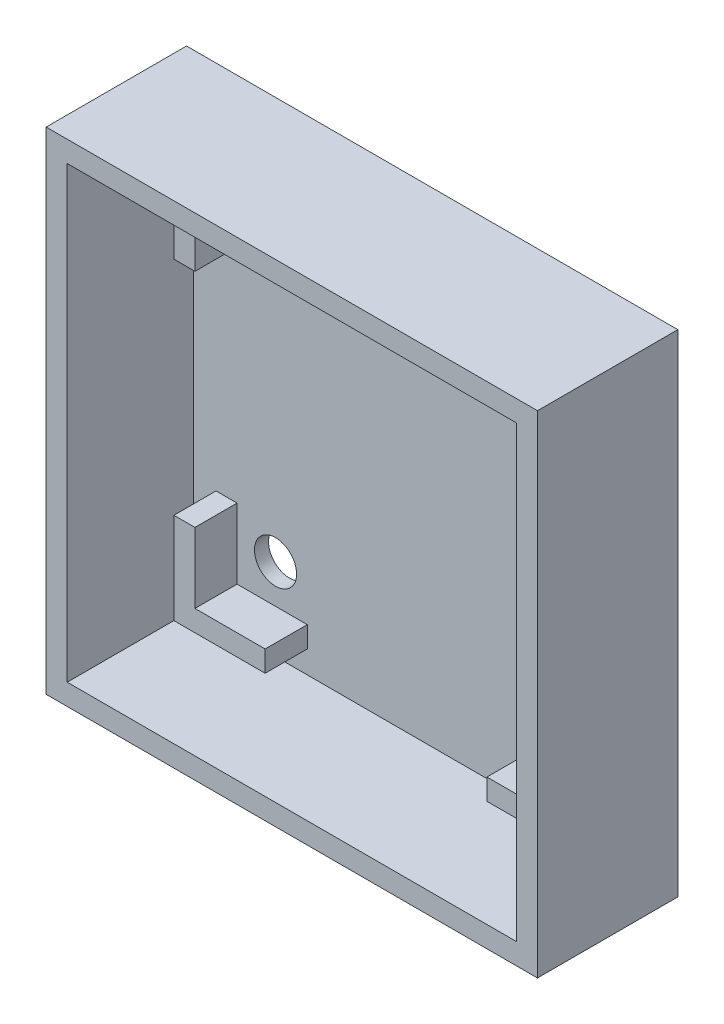
SolidWorks part; units mm, degrees
ref_plane "Front Plane" through (0, 0, 0) normal (0, 0, 1) x (1, 0, 0)
ref_plane "Top Plane" through (0, 0, 0) normal (0, 1, 0) x (1, 0, 0)
ref_plane "Right Plane" through (0, 0, 0) normal (1, 0, 0) x (0, 0, -1)
sketch "Sketch1" plane through (0, 0, 0) normal (0, 0, 1) x (1, 0, 0)
  line L1 (0, 0) -> (35, 0)
  line L2 (0, 0) -> (0, -35)
  line L3 (0, -35) -> (35, -35)
  line L4 (35, 0) -> (35, -35)
  dimension "D1" = 35
  dimension "D2" = 35
extrude "Boss-Extrude1" add sketch "Sketch1" along normal blind 10
sketch "Sketch2" plane through (0, 0, 10) normal (0, 0, 1) x (1, 0, 0)
  line L0 (0, 0) -> (1.5, 0) construction
  line L1 (35, 0) -> (0, 0) construction
  line L2 (1.5, 0) -> (1.5, -1.5) construction
  line L3 (1.5, -1.5) -> (1.5, -33.5)
  line L5 (1.5, -33.5) -> (33.5, -33.5)
  line L6 (33.5, -33.5) -> (33.5, -1.5)
  line L7 (33.5, -1.5) -> (1.5, -1.5)
  dimension "D1" = 1.5
  dimension "D2" = 1.5
  dimension "D3" = 32
  dimension "D4" = 32
extrude "Cut-Extrude1" cut sketch "Sketch2" against normal blind 9
sketch "Sketch3" plane through (0, 0, 1) normal (0, 0, 1) x (1, 0, 0)
  line L0 (1.5, -1.5) -> (33.5, -33.5) construction
  line L1 (1.5, -33.5) -> (33.5, -1.5) construction
  line L2 (4.6, -4.6) -> (9.6, -4.6)
  line L3 (4.6, -4.6) -> (9.6, -4.6)
  line L4 (4.6, -4.6) -> (4.6, -9.6)
  line L7 (4.6, -4.6) -> (30.4, -30.4) construction
  line L8 (4.6, -30.4) -> (30.4, -4.6) construction
  line L9 (9.6, -4.6) -> (9.6, -3.1)
  line L10 (9.6, -3.1) -> (3.1, -3.1)
  line L11 (3.1, -3.1) -> (3.1, -9.6)
  line L12 (3.1, -9.6) -> (4.6, -9.6)
  line L13 (0, -17.5) -> (35, -17.5) construction
  line L14 (0, 0) -> (0, -35) construction
  line L15 (35, -35) -> (35, 0) construction
  line L16 (30.4, -30.4) -> (25.4, -30.4)
  line L17 (25.4, -31.9) -> (25.4, -30.4)
  line L18 (31.9, -31.9) -> (25.4, -31.9)
  line L19 (31.9, -25.4) -> (31.9, -31.9)
  line L20 (30.4, -25.4) -> (31.9, -25.4)
  line L21 (30.4, -30.4) -> (30.4, -25.4)
  line L22 (4.6, -30.4) -> (4.6, -25.4)
  line L23 (3.1, -25.4) -> (4.6, -25.4)
  line L24 (3.1, -31.9) -> (3.1, -25.4)
  line L25 (9.6, -31.9) -> (3.1, -31.9)
  line L26 (9.6, -30.4) -> (9.6, -31.9)
  line L27 (4.6, -30.4) -> (9.6, -30.4)
  line L28 (30.4, -4.6) -> (30.4, -9.6)
  line L29 (30.4, -9.6) -> (31.9, -9.6)
  line L30 (31.9, -9.6) -> (31.9, -3.1)
  line L31 (31.9, -3.1) -> (25.4, -3.1)
  line L32 (25.4, -3.1) -> (25.4, -4.6)
  line L33 (30.4, -4.6) -> (25.4, -4.6)
  point P8 (17.5, -17.5)
  point P44 (17.5, -7.34)
  point P54 (17.5, -17.5)
  dimension "D1" = 25.8
  dimension "D2" = 25.8
  dimension "D3" = 1.5
  dimension "D4" = 1.5
  dimension "D5" = 6.5
  dimension "D6" = 6.5
extrude "Boss-Extrude2" add sketch "Sketch3" along normal blind 3 contours L11 L12 L4 L2 L9 L10 | L27 L22 L23 L24 L25 L26 | L21 L16 L17 L18 L19 L20 | L33 L28 L29 L30 L31 L32
sketch "Sketch5" plane through (0, 0, 1) normal (0, 0, 1) x (1, 0, 0)
  line L0 (0, -35) -> (35, 0) construction
  line L1 (35, -35) -> (0, 0) construction
  line L2 (17.5, -17.5) -> (17.5, -7.34) construction
  line L3 (7.34, -7.34) -> (27.66, -7.34) construction
  circle A0 centre (7.34, -7.34) radius 1.5
  circle A1 centre (27.66, -7.34) radius 1.5
  circle A2 centre (27.66, -27.66) radius 1.5
  circle A3 centre (7.34, -27.66) radius 1.5
  point P12 (17.5, -7.34)
  point P23 (17.5, -17.5)
  dimension "D2" = 4
  dimension "D1" = 10.16
extrude "Cut-Extrude2" cut sketch "Sketch5" against normal through all contours A0 | A3 | A2 | A1
